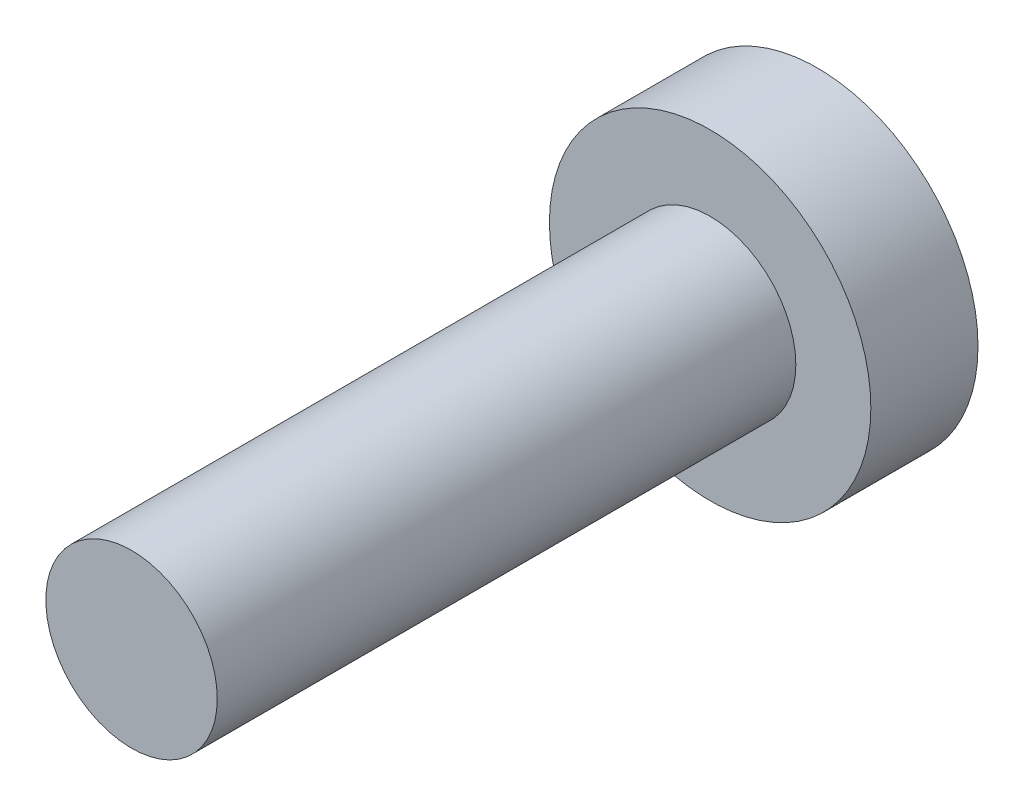
SolidWorks part; units mm, degrees
material "AISI 304"
ref_plane "Alzado" through (0, 0, 0) normal (0, 0, 1) x (1, 0, 0)
ref_plane "Planta" through (0, 0, 0) normal (0, 1, 0) x (1, 0, 0)
ref_plane "Vista lateral" through (0, 0, 0) normal (1, 0, 0) x (0, 0, -1)
sketch "Sk_Cabeza_avellanada" plane through (0, 0, 0) normal (0, 0, 1) x (1, 0, 0)
  circle A0 centre (0, 0) radius 3.75
  dimension "D1" = 7.5
extrude "Cabeza_avellanada" add sketch "Sk_Cabeza_avellanada" along normal blind 2.5
sketch "Sk_Cuerpo" plane through (0, 0, 0) normal (0, 0, 1) x (1, 0, 0)
  circle A0 centre (0, 0) radius 2
  dimension "D1" = 4
extrude "Cuerpo" add sketch "Sk_Cuerpo" along normal blind 16
sketch "Sk_Hexagono_interior" plane through (0, 0, 0) normal (0, 0, 1) x (1, 0, 0)
  line L1 (0, -1.4434) -> (1.25, -0.7217)
  line L2 (1.25, -0.7217) -> (1.25, 0.7217)
  line L3 (1.25, 0.7217) -> (0, 1.4434)
  line L4 (0, 1.4434) -> (-1.25, 0.7217)
  line L5 (-1.25, 0.7217) -> (-1.25, -0.7217)
  line L6 (-1.25, -0.7217) -> (0, -1.4434)
  circle A0 centre (0, 0) radius 1.25 construction
  dimension "D1" = 2.5
extrude "Hexagono_interior" cut sketch "Sk_Hexagono_interior" along normal blind 1.5
